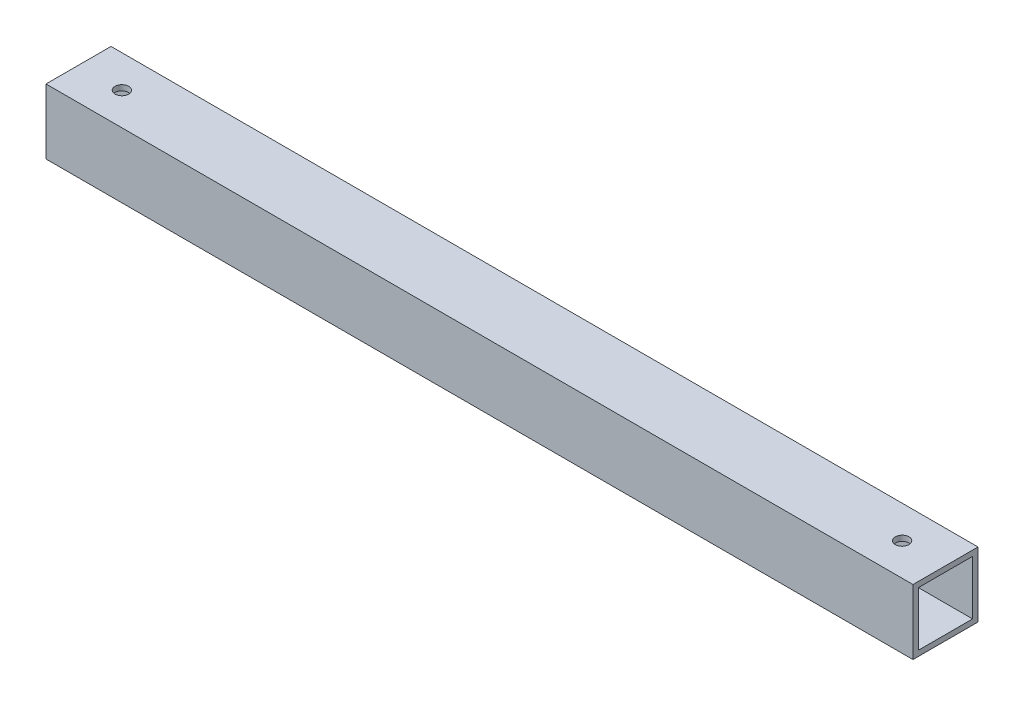
SolidWorks part; units mm, degrees
ref_plane "Front Plane" through (0, 0, 0) normal (0, 0, 1) x (1, 0, 0)
ref_plane "Top Plane" through (0, 0, 0) normal (0, 1, 0) x (1, 0, 0)
ref_plane "Right Plane" through (0, 0, 0) normal (1, 0, 0) x (0, 0, -1)
sketch "Sketch1" plane through (0, 0, 0) normal (1, 0, 0) x (0, 0, -1)
  line L1 (-7.9375, -7.9375) -> (7.9375, -7.9375)
  line L2 (-7.9375, -7.9375) -> (-7.9375, 7.9375)
  line L3 (-7.9375, 7.9375) -> (7.9375, 7.9375)
  line L4 (7.9375, -7.9375) -> (7.9375, 7.9375)
  line L5 (-7.9375, -7.9375) -> (7.9375, 7.9375) construction
  line L6 (-7.9375, 7.9375) -> (7.9375, -7.9375) construction
  line L7 (-9.525, -9.525) -> (9.525, -9.525)
  line L8 (-9.525, -9.525) -> (-9.525, 9.525)
  line L9 (-9.525, 9.525) -> (9.525, 9.525)
  line L10 (9.525, -9.525) -> (9.525, 9.525)
  line L11 (-9.525, -9.525) -> (9.525, 9.525) construction
  line L12 (-9.525, 9.525) -> (9.525, -9.525) construction
  point P0 (0, 0)
  point P6 (0, 0)
  dimension "D1" = 19.05
  dimension "D2" = 1.5875
extrude "Boss-Extrude1" add sketch "Sketch1" along normal blind 254
sketch "Sketch2" plane through (0, 9.525, 0) normal (0, 1, 0) x (1, 0, 0)
  line L0 (0, 0) -> (12.7, 0) construction
  line L1 (12.7, 0) -> (241.3, 0) construction
  line L2 (241.3, 0) -> (254, 0) construction
  line L3 (254, 9.525) -> (254, -9.525) construction
  circle A0 centre (12.7, 0) radius 2
  circle A1 centre (241.3, 0) radius 2
  dimension "D1" = 4
  dimension "D2" = 228.6
extrude "Cut-Extrude1" cut sketch "Sketch2" against normal through all
